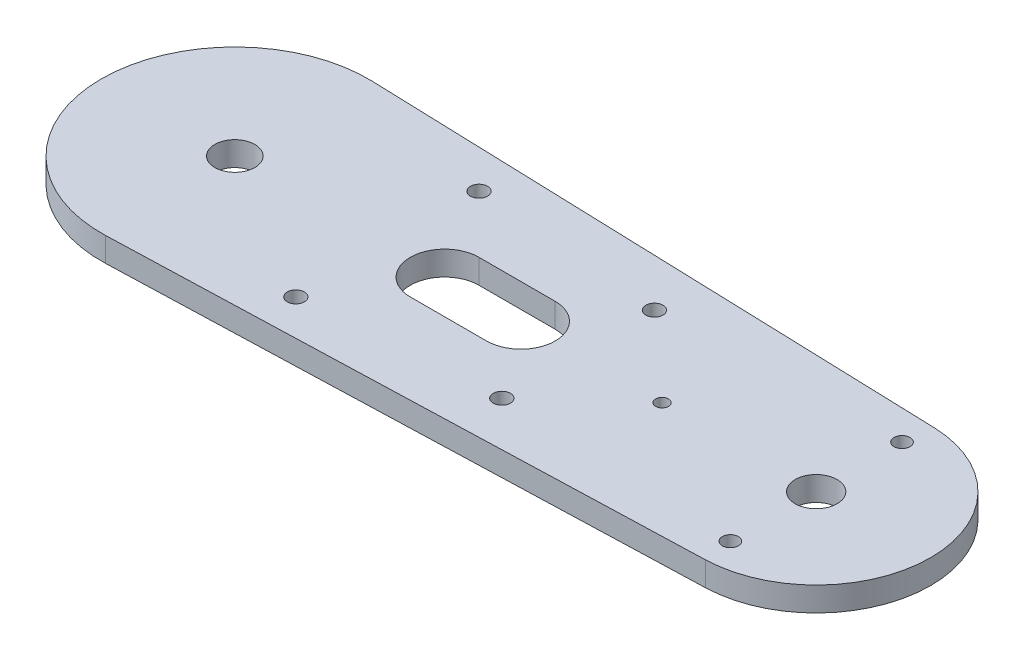
SolidWorks part; units mm, degrees
material "Aleación 6061"
ref_plane "Alzado" through (0, 0, 0) normal (0, 0, 1) x (1, 0, 0)
ref_plane "Planta" through (0, 0, 0) normal (0, 1, 0) x (1, 0, 0)
ref_plane "Vista lateral" through (0, 0, 0) normal (1, 0, 0) x (0, 0, -1)
sketch "Croquis1" plane through (0, 0, 0) normal (0, 1, 0) x (1, 0, 0)
  line L0 (1.1483, -206.4312) -> (153.3843, -201.4338)
  line L1 (153.3843, -201.4338) -> (153.3843, -141.4662)
  line L2 (153.3843, -141.4662) -> (1.1483, -136.4688)
  line L3 (1.1483, -136.4688) -> (1.1483, -206.4312)
  dimension "D1" = 1.1483
  dimension "D2" = 206.4312
  dimension "D3" = 153.3843
  dimension "D4" = 201.4338
  dimension "D5" = 153.3843
  dimension "D6" = 141.4662
  dimension "D7" = 1.1483
  dimension "D8" = 136.4688
extrude "Placa" add sketch "Croquis1" along normal blind 6.35 from offset 10.35
sketch "Croquis2" plane through (0, 0, 0) normal (0, 1, 0) x (1, 0, 0)
  circle A0 centre (0, -171.45) radius 35
  dimension "D1" = 70
  dimension "D2" = 171.45
extrude "Placa_r1" add sketch "Croquis2" along normal blind 6.35 from offset 10.35
sketch "Croquis3" plane through (0, 0, 0) normal (0, 1, 0) x (1, 0, 0)
  circle A0 centre (152.4, -171.45) radius 30
  dimension "D1" = 60
  dimension "D2" = 152.4
  dimension "D3" = 171.45
extrude "Placa_r2" add sketch "Croquis3" along normal blind 6.35 from offset 10.35
sketch "Croquis4" plane through (0, 0, 0) normal (0, 1, 0) x (1, 0, 0)
  line L0 (55, -162.45) -> (75, -162.45)
  line L1 (75, -180.45) -> (55, -180.45)
  arc A0 (75, -162.45) -> (75, -180.45) centre (75, -171.45) cw
  arc A1 (55, -180.45) -> (55, -162.45) centre (55, -171.45) cw
  dimension "D1" = 9
  dimension "D2" = 9
  dimension "D3" = 55
  dimension "D4" = 162.45
  dimension "D5" = 75
  dimension "D6" = 162.45
  dimension "D7" = 75
  dimension "D8" = 180.45
  dimension "D9" = 55
  dimension "D10" = 180.45
extrude "Aligerado" cut sketch "Croquis4" along normal blind 6.35 from offset 10.35
sketch "Croquis5" plane through (0, 0, 0) normal (0, 1, 0) x (1, 0, 0)
  circle A0 centre (40, -195.45) radius 2.25
  circle A1 centre (40, -147.45) radius 2.25
  circle A2 centre (90, -191.45) radius 2.25
  circle A3 centre (90, -151.45) radius 2.25
  dimension "D1" = 4.5
  dimension "D2" = 4.5
  dimension "D3" = 4.5
  dimension "D4" = 4.5
  dimension "D5" = 40
  dimension "D6" = 195.45
  dimension "D7" = 40
  dimension "D8" = 147.45
  dimension "D9" = 90
  dimension "D10" = 191.45
  dimension "D11" = 90
  dimension "D12" = 151.45
extrude "Barrenos_separadores_M4" cut sketch "Croquis5" along normal blind 6.35 from offset 10.35
sketch "Croquis6" plane through (0, 0, 0) normal (0, 1, 0) x (1, 0, 0)
  circle A0 centre (0, -171.45) radius 5.25
  circle A1 centre (152.4, -171.45) radius 5.5
  circle A2 centre (152.4, -193.95) radius 2.1
  circle A3 centre (152.4, -148.95) radius 2.1
  dimension "D1" = 10.5
  dimension "D2" = 11
  dimension "D3" = 4.2
  dimension "D4" = 4.2
  dimension "D5" = 171.45
  dimension "D6" = 152.4
  dimension "D7" = 171.45
  dimension "D8" = 152.4
  dimension "D9" = 193.95
  dimension "D10" = 152.4
  dimension "D11" = 148.95
extrude "Paso_pernos_y_rosca_M5_KFL000" cut sketch "Croquis6" along normal blind 6.35 from offset 10.35
sketch "Croquis7" plane through (0, 0, 0) normal (0, 1, 0) x (1, 0, 0)
  circle A0 centre (112, -171.45) radius 1.25
  dimension "D1" = 2.5
  dimension "D2" = 112
  dimension "D3" = 171.45
extrude "Rosca_M3_bases_cincho" cut sketch "Croquis7" along normal blind 6.35 from offset 10.35
sketch "Croquis8" plane through (0, 0, 0) normal (0, 1, 0) x (1, 0, 0)
  circle A0 centre (112, -171.45) radius 1.7
  dimension "D1" = 3.4
  dimension "D2" = 112
  dimension "D3" = 171.45
extrude "Paso_M3_bases_cincho" cut sketch "Croquis8" along normal blind 6.35 from offset 10.35
